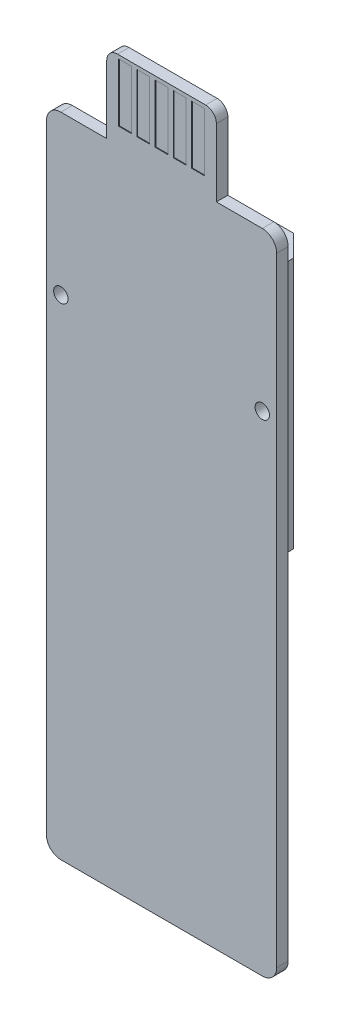
SolidWorks part; units mm, degrees
ref_plane "前视基准面" through (0, 0, 0) normal (0, 0, 1) x (1, 0, 0)
ref_plane "上视基准面" through (0, 0, 0) normal (0, 1, 0) x (1, 0, 0)
ref_plane "右视基准面" through (0, 0, 0) normal (1, 0, 0) x (0, 0, -1)
other "Configuration Table"
sketch "草图1" plane through (0, 0, 0) normal (0, 0, 1) x (1, 0, 0)
  line L1 (-14, 50) -> (14, 50)
  line L2 (-16, 48) -> (-16, -48)
  line L3 (-14, -50) -> (14, -50)
  line L4 (16, 48) -> (16, -48)
  arc A0 (-14, 50) -> (-16, 48) centre (-14, 48) ccw
  arc A1 (16, 48) -> (14, 50) centre (14, 48) ccw
  arc A2 (-16, -48) -> (-14, -50) centre (-14, -48) ccw
  arc A3 (14, -50) -> (16, -48) centre (14, -48) ccw
  circle A4 centre (-14, -48) radius 1
  circle A5 centre (14, -48) radius 1
  point P0 (0, 0)
  dimension "D3" = 4
  dimension "D4" = 4
  dimension "D5" = 4
  dimension "D6" = 4
  dimension "D7" = 2
  dimension "D8" = 2
  dimension "D9" = 32
  dimension "D10" = 100
  dimension "D11" = 50
  dimension "D12" = 16
extrude "凸台-拉伸1" add sketch "草图1" along normal blind 1.6
sketch "草图2" plane through (0, 0, 0) normal (0, 0, 1) x (1, 0, 0)
  line L0 (16, -48) -> (16, 48) construction
  line L1 (-16, 30) -> (16, 30) construction
  line L2 (-16, 30) -> (-16, 0) construction
  line L3 (-16, 0) -> (16, 0) construction
  line L4 (16, 30) -> (16, 0) construction
  line L5 (-16, 48) -> (-16, -48) construction
  circle A0 centre (-14, 28) radius 2 construction
  circle A1 centre (14, 28) radius 2 construction
  circle A2 centre (-14, 28) radius 1
  circle A3 centre (14, 28) radius 1
  dimension "D2" = 4
  dimension "D3" = 4
  dimension "D4" = 2
  dimension "D5" = 2
  dimension "D1" = 30
extrude "切除-拉伸1" cut sketch "草图2" along normal up to surface (1.6 mm away) from surface at 0 up to face at (-13, -48, 1.6) starting at face at (0, 0, 0)
sketch "草图3" plane through (0, 0, 0) normal (0, 0, 1) x (1, 0, 0)
  line L0 (14, 50) -> (-14, 50) construction
  line L1 (-7.62, 60.92) -> (7.62, 60.92) construction
  line L2 (-7.62, 60.92) -> (-7.62, 50) construction
  line L3 (-7.62, 50) -> (7.62, 50)
  line L4 (7.62, 60.92) -> (7.62, 50) construction
  line L5 (-6.12, 60.92) -> (6.12, 60.92)
  line L6 (7.62, 59.42) -> (7.62, 50)
  line L7 (-7.62, 59.42) -> (-7.62, 50)
  line L8 (-1000, 0) -> (49000, 0) construction
  line L9 (7.62, -60.92) -> (7.62, -50) construction
  line L10 (-7.62, -60.92) -> (-7.62, -50) construction
  line L11 (-7.62, -60.92) -> (7.62, -60.92) construction
  line L12 (-7.62, -59.42) -> (-7.62, -50)
  line L13 (7.62, -59.42) -> (7.62, -50)
  line L14 (-6.12, -60.92) -> (6.12, -60.92)
  line L15 (-7.62, -50) -> (7.62, -50)
  arc A0 (-6.12, 60.92) -> (-7.62, 59.42) centre (-6.12, 59.42) ccw
  arc A1 (7.62, 59.42) -> (6.12, 60.92) centre (6.12, 59.42) ccw
  arc A2 (7.62, -59.42) -> (6.12, -60.92) centre (6.12, -59.42) cw
  arc A3 (-6.12, -60.92) -> (-7.62, -59.42) centre (-6.12, -59.42) cw
  point P6 (0, 60.92)
  dimension "D3" = 3
  dimension "D4" = 3
  dimension "D1" = 10.92
  dimension "D2" = 15.24
extrude "凸台-拉伸2" add sketch "草图3" against normal up to surface (1.6 mm away) from surface at 1.6 up to face at (-13, 28, 0) starting at face at (-13, 28, 1.6)
sketch "草图4" plane through (0, 0, 0) normal (0, 0, 1) x (1, 0, 0)
  line L0 (-6.12, 60.92) -> (6.12, 60.92) construction
  line L1 (-0.89, 60.42) -> (0.89, 60.42)
  line L2 (-0.89, 60.42) -> (-0.89, 52.32)
  line L3 (-0.89, 52.32) -> (0.89, 52.32)
  line L4 (0.89, 60.42) -> (0.89, 52.32)
  line L5 (1.65, 60.42) -> (3.43, 60.42)
  line L6 (1.65, 60.42) -> (1.65, 52.32)
  line L7 (1.65, 52.32) -> (3.43, 52.32)
  line L8 (3.43, 60.42) -> (3.43, 52.32)
  line L9 (4.19, 60.42) -> (5.97, 60.42)
  line L10 (4.19, 60.42) -> (4.19, 52.32)
  line L11 (4.19, 52.32) -> (5.97, 52.32)
  line L12 (5.97, 60.42) -> (5.97, 52.32)
  line L13 (-0.89, 60.42) -> (1.65, 60.42) construction
  line L14 (-3.43, 60.42) -> (-3.43, 52.32)
  line L15 (-3.43, 60.42) -> (-1.65, 60.42)
  line L16 (-1.65, 60.42) -> (-1.65, 52.32)
  line L17 (-3.43, 52.32) -> (-1.65, 52.32)
  line L18 (-5.97, 60.42) -> (-5.97, 52.32)
  line L19 (-5.97, 60.42) -> (-4.19, 60.42)
  line L20 (-4.19, 60.42) -> (-4.19, 52.32)
  line L21 (-5.97, 52.32) -> (-4.19, 52.32)
  line L22 (-0.89, 60.42) -> (-3.43, 60.42) construction
  line L23 (-1000, 0) -> (49000, 0) construction
  line L24 (-0.89, -60.42) -> (-3.43, -60.42) construction
  line L25 (-0.89, -60.42) -> (1.65, -60.42) construction
  line L26 (-5.97, -52.32) -> (-4.19, -52.32)
  line L27 (-4.19, -60.42) -> (-4.19, -52.32)
  line L28 (-5.97, -60.42) -> (-4.19, -60.42)
  line L29 (-5.97, -60.42) -> (-5.97, -52.32)
  line L30 (-3.43, -52.32) -> (-1.65, -52.32)
  line L31 (-1.65, -60.42) -> (-1.65, -52.32)
  line L32 (-3.43, -60.42) -> (-1.65, -60.42)
  line L33 (-3.43, -60.42) -> (-3.43, -52.32)
  line L34 (5.97, -60.42) -> (5.97, -52.32)
  line L35 (4.19, -52.32) -> (5.97, -52.32)
  line L36 (4.19, -60.42) -> (4.19, -52.32)
  line L37 (4.19, -60.42) -> (5.97, -60.42)
  line L38 (3.43, -60.42) -> (3.43, -52.32)
  line L39 (1.65, -52.32) -> (3.43, -52.32)
  line L40 (1.65, -60.42) -> (1.65, -52.32)
  line L41 (1.65, -60.42) -> (3.43, -60.42)
  line L42 (0.89, -60.42) -> (0.89, -52.32)
  line L43 (-0.89, -52.32) -> (0.89, -52.32)
  line L44 (-0.89, -60.42) -> (-0.89, -52.32)
  line L45 (-0.89, -60.42) -> (0.89, -60.42)
  point P6 (0, 60.42)
  dimension "D1" = 8.1
  dimension "D2" = 1.78
  dimension "D3" = 0.5
  dimension "D5" = 2.54
  dimension "D7" = 2.54
  dimension "D4" = 3
  dimension "D6" = 3
extrude "切除-拉伸2" cut sketch "草图4" along normal blind 0.1 from surface at 0 starting at face at (-13, 28, 0)
sketch "草图5" plane through (0, 0, 0) normal (0, 0, 1) x (1, 0, 0)
  line L4 (3.43, 60.42) -> (1.65, 60.42)
  line L5 (3.43, 52.32) -> (3.43, 60.42)
  line L6 (1.65, 52.32) -> (3.43, 52.32)
  line L7 (1.65, 60.42) -> (1.65, 52.32)
  line L8 (3.43, 60.42) -> (1.65, 60.42)
  line L9 (3.43, 52.32) -> (3.43, 60.42)
  line L10 (1.65, 52.32) -> (3.43, 52.32)
  line L11 (1.65, 60.42) -> (1.65, 52.32)
  line L12 (0.89, 60.42) -> (-0.89, 60.42)
  line L13 (0.89, 52.32) -> (0.89, 60.42)
  line L14 (-0.89, 52.32) -> (0.89, 52.32)
  line L15 (-0.89, 60.42) -> (-0.89, 52.32)
  line L16 (0.89, 60.42) -> (-0.89, 60.42)
  line L17 (0.89, 52.32) -> (0.89, 60.42)
  line L18 (-0.89, 52.32) -> (0.89, 52.32)
  line L19 (-0.89, 60.42) -> (-0.89, 52.32)
  line L20 (-5.97, 60.42) -> (-5.97, 52.32)
  line L21 (-5.97, 52.32) -> (-4.19, 52.32)
  line L22 (-4.19, 52.32) -> (-4.19, 60.42)
  line L23 (-4.19, 60.42) -> (-5.97, 60.42)
  line L24 (-5.97, 60.42) -> (-5.97, 52.32)
  line L25 (-5.97, 52.32) -> (-4.19, 52.32)
  line L26 (-4.19, 52.32) -> (-4.19, 60.42)
  line L27 (-4.19, 60.42) -> (-5.97, 60.42)
  line L28 (-3.43, 60.42) -> (-3.43, 52.32)
  line L29 (-1.65, 60.42) -> (-3.43, 60.42)
  line L30 (-1.65, 52.32) -> (-1.65, 60.42)
  line L31 (-3.43, 52.32) -> (-1.65, 52.32)
  line L32 (-3.43, 60.42) -> (-3.43, 52.32)
  line L33 (-1.65, 60.42) -> (-3.43, 60.42)
  line L34 (-1.65, 52.32) -> (-1.65, 60.42)
  line L35 (-3.43, 52.32) -> (-1.65, 52.32)
  line L36 (5.97, 60.42) -> (4.19, 60.42)
  line L37 (4.19, 60.42) -> (4.19, 52.32)
  line L38 (4.19, 52.32) -> (5.97, 52.32)
  line L39 (5.97, 52.32) -> (5.97, 60.42)
  line L40 (5.97, 60.42) -> (4.19, 60.42)
  line L41 (4.19, 60.42) -> (4.19, 52.32)
  line L42 (4.19, 52.32) -> (5.97, 52.32)
  line L43 (5.97, 52.32) -> (5.97, 60.42)
  line L44 (3.43, -60.42) -> (3.43, -52.32)
  line L45 (3.43, -52.32) -> (1.65, -52.32)
  line L46 (1.65, -52.32) -> (1.65, -60.42)
  line L47 (1.65, -60.42) -> (3.43, -60.42)
  line L48 (3.43, -60.42) -> (3.43, -52.32)
  line L49 (3.43, -52.32) -> (1.65, -52.32)
  line L50 (1.65, -52.32) -> (1.65, -60.42)
  line L51 (1.65, -60.42) -> (3.43, -60.42)
  line L52 (5.97, -60.42) -> (5.97, -52.32)
  line L53 (5.97, -52.32) -> (4.19, -52.32)
  line L54 (4.19, -52.32) -> (4.19, -60.42)
  line L55 (4.19, -60.42) -> (5.97, -60.42)
  line L56 (5.97, -60.42) -> (5.97, -52.32)
  line L57 (5.97, -52.32) -> (4.19, -52.32)
  line L58 (4.19, -52.32) -> (4.19, -60.42)
  line L59 (4.19, -60.42) -> (5.97, -60.42)
  line L60 (-1.65, -52.32) -> (-3.43, -52.32)
  line L61 (-1.65, -60.42) -> (-1.65, -52.32)
  line L62 (-3.43, -60.42) -> (-1.65, -60.42)
  line L63 (-3.43, -52.32) -> (-3.43, -60.42)
  line L64 (-1.65, -52.32) -> (-3.43, -52.32)
  line L65 (-1.65, -60.42) -> (-1.65, -52.32)
  line L66 (-3.43, -60.42) -> (-1.65, -60.42)
  line L67 (-3.43, -52.32) -> (-3.43, -60.42)
  line L68 (-4.19, -52.32) -> (-5.97, -52.32)
  line L69 (-4.19, -60.42) -> (-4.19, -52.32)
  line L70 (-5.97, -60.42) -> (-4.19, -60.42)
  line L71 (-5.97, -52.32) -> (-5.97, -60.42)
  line L72 (-4.19, -52.32) -> (-5.97, -52.32)
  line L73 (-4.19, -60.42) -> (-4.19, -52.32)
  line L74 (-5.97, -60.42) -> (-4.19, -60.42)
  line L75 (-5.97, -52.32) -> (-5.97, -60.42)
  line L76 (0.89, -52.32) -> (-0.89, -52.32)
  line L77 (-0.89, -52.32) -> (-0.89, -60.42)
  line L78 (-0.89, -60.42) -> (0.89, -60.42)
  line L79 (0.89, -60.42) -> (0.89, -52.32)
  line L80 (0.89, -52.32) -> (-0.89, -52.32)
  line L81 (-0.89, -52.32) -> (-0.89, -60.42)
  line L82 (-0.89, -60.42) -> (0.89, -60.42)
  line L83 (0.89, -60.42) -> (0.89, -52.32)
  dimension "D1" = 0
  dimension "D2" = 0
  dimension "D3" = 0
  dimension "D4" = 0
  dimension "D5" = 0
  dimension "D6" = 0
  dimension "D7" = 0
  dimension "D8" = 0
  dimension "D9" = 0
  dimension "D10" = 0
extrude "切除-拉伸3" cut sketch "草图5" against normal blind 0.1 from surface at 1.6 starting at face at (-13, 28, 1.6)
sketch "草图6" plane through (0, 0, 0) normal (0, 0, 1) x (1, 0, 0)
  line L0 (-14, -50) -> (-7.62, -50) construction
  line L1 (-9.75, 40) -> (9.75, 40)
  line L2 (-9.75, 40) -> (-9.75, -30)
  line L3 (-9.75, -30) -> (9.75, -30)
  line L4 (9.75, 40) -> (9.75, -30)
  point P6 (0, -30)
  dimension "D1" = 19.5
  dimension "D2" = 70
  dimension "D3" = 20
extrude "凸台-拉伸3" add sketch "草图6" against normal blind 10
sketch "草图7" plane through (0, 0, 0) normal (0, 1, 0) x (1, 0, 0)
  line L0 (9.75, 10) -> (9.75, 7)
  line L1 (9.75, 10) -> (9.75, 0) construction
  line L2 (9.75, 7) -> (6.75, 10)
  line L3 (9.75, 10) -> (-9.75, 10) construction
  line L4 (6.75, 10) -> (9.75, 10)
  line L5 (-9.75, 10) -> (-6.75, 10)
  line L6 (-6.75, 10) -> (-9.75, 7)
  line L7 (-9.75, 10) -> (-9.75, 0) construction
  line L8 (-9.75, 7) -> (-9.75, 10)
  dimension "D1" = 3
  dimension "D2" = 3
  dimension "D3" = 3
  dimension "D4" = 3
extrude "切除-拉伸4" cut sketch "草图7" against normal up to surface (70 mm away) from surface at 40 up to face at (0, -30, -5) starting at face at (0, 40, -5)
sketch "草图9" plane through (0, 0, 0) normal (0, 0, 1) x (1, 0, 0)
  line L0 (9.75, -30) -> (9.75, 40) construction
  line L1 (-9.75, -30) -> (9.75, -30)
  line L2 (-9.75, -30) -> (-9.75, 5)
  line L3 (-9.75, 5) -> (9.75, 5)
  line L4 (9.75, -30) -> (9.75, 5)
  dimension "D1" = 35
extrude "切除-拉伸5" cut sketch "草图9" along normal blind 4 from surface at -10 starting at face at (0, 5, -10)
sketch "草图11" plane through (0, 0, 0) normal (0, 0, 1) x (1, 0, 0)
  line L0 (16, -48) -> (16, 48) construction
  line L1 (-16, 50) -> (16, 50) construction
  line L2 (-16, 50) -> (-16, -40) construction
  line L3 (-16, -40) -> (16, -40) construction
  line L4 (16, 50) -> (16, -40) construction
  line L5 (-16, 48) -> (-16, -48) construction
  line L6 (14, 50) -> (7.62, 50) construction
  line L7 (7.62, -50) -> (14, -50) construction
  line L8 (7.62, -50) -> (7.62, -59.42) construction
  line L9 (6.12, -60.92) -> (-6.12, -60.92) construction
  line L10 (-7.62, -59.42) -> (-7.62, -50) construction
  line L11 (-14, -50) -> (-7.62, -50) construction
  line L12 (-16, 48) -> (-16, -48) construction
  line L13 (16, -48) -> (16, 48) construction
  line L14 (7.62, -50) -> (14, -50)
  line L15 (7.62, -50) -> (7.62, -59.42)
  line L16 (6.12, -60.92) -> (-6.12, -60.92)
  line L17 (-7.62, -59.42) -> (-7.62, -50)
  line L18 (-14, -50) -> (-7.62, -50)
  line L19 (16, -38) -> (16, -48)
  line L20 (-14, -40) -> (14, -40)
  line L21 (-16, -38) -> (-16, -48)
  arc A0 (-16, -38) -> (-14, -40) centre (-14, -38) ccw
  arc A1 (14, -40) -> (16, -38) centre (14, -38) ccw
  arc A2 (14, -50) -> (16, -48) centre (14, -48) ccw construction
  arc A3 (6.12, -60.92) -> (7.62, -59.42) centre (6.12, -59.42) ccw construction
  arc A4 (-7.62, -59.42) -> (-6.12, -60.92) centre (-6.12, -59.42) ccw construction
  arc A5 (-16, -48) -> (-14, -50) centre (-14, -48) ccw construction
  arc A6 (14, -50) -> (16, -48) centre (14, -48) ccw
  arc A7 (6.12, -60.92) -> (7.62, -59.42) centre (6.12, -59.42) ccw
  arc A8 (-7.62, -59.42) -> (-6.12, -60.92) centre (-6.12, -59.42) ccw
  arc A9 (-16, -48) -> (-14, -50) centre (-14, -48) ccw
  dimension "D5" = 4
  dimension "D6" = 4
  dimension "D1" = 0
  dimension "D2" = 0
  dimension "D3" = 0
  dimension "D4" = 90
extrude "切除-拉伸6" cut sketch "草图11" along normal up to surface (1.6 mm away) up to face at (-13, 28, 1.6)
